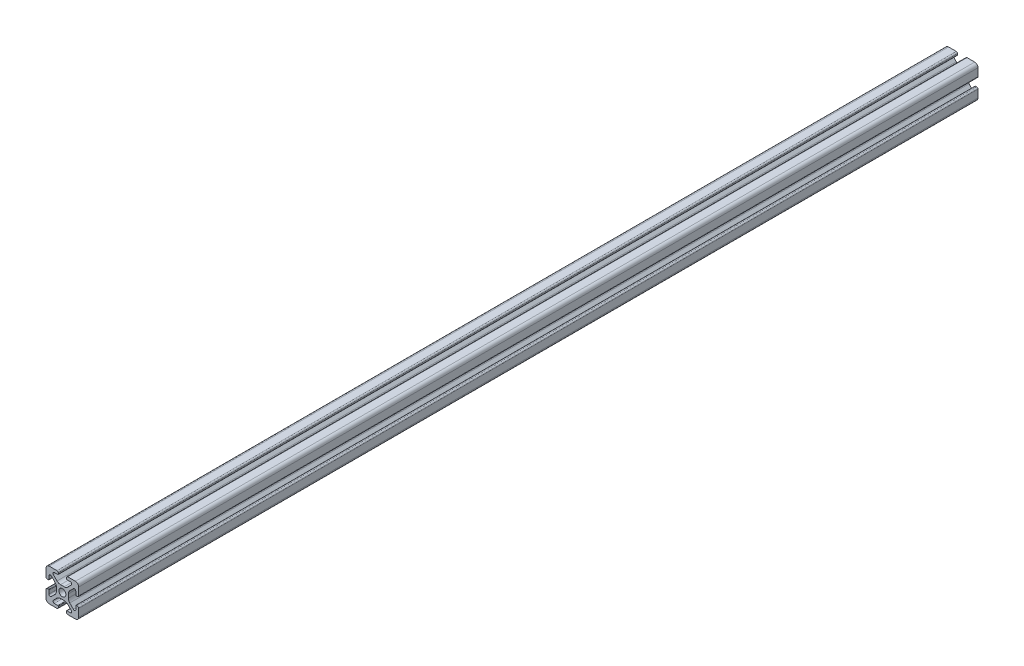
SolidWorks part; units mm, degrees
material "Alliage 1060"
ref_plane "Plan de face" through (0, 0, 0) normal (0, 0, 1) x (1, 0, 0)
ref_plane "Plan de dessus" through (0, 0, 0) normal (0, 1, 0) x (1, 0, 0)
ref_plane "Plan de droite" through (0, 0, 0) normal (1, 0, 0) x (0, 0, -1)
sketch "Esquisse1" plane through (0, 0, 0) normal (0, 0, 1) x (1, 0, 0)
  line L108 (-3.2559, 4.5287) -> (-5.5062, 6.779)
  line L109 (-4.9176, 8.2) -> (-2.8, 8.2)
  line L110 (-2.5, 8.5) -> (-2.5, 9.2)
  line L111 (-3.3, 10) -> (-8, 10)
  line L112 (-10, 8) -> (-10, 3.3)
  line L113 (-9.2, 2.5) -> (-8.5, 2.5)
  line L114 (-8.2, 2.8) -> (-8.2, 4.9176)
  line L115 (-6.779, 5.5062) -> (-4.5287, 3.2559)
  line L116 (-3.65, 1.1346) -> (-3.65, -1.1346)
  line L117 (-4.5287, -3.2559) -> (-6.779, -5.5062)
  line L118 (-8.2, -4.9176) -> (-8.2, -2.8)
  line L119 (-8.5, -2.5) -> (-9.2, -2.5)
  line L120 (-10, -3.3) -> (-10, -8)
  line L121 (-8, -10) -> (-3.3, -10)
  line L122 (-2.5, -9.2) -> (-2.5, -8.5)
  line L123 (-2.8, -8.2) -> (-4.9176, -8.2)
  line L124 (-5.5062, -6.779) -> (-3.2559, -4.5287)
  line L125 (-1.1346, -3.65) -> (1.1346, -3.65)
  line L126 (3.2559, -4.5287) -> (5.5062, -6.779)
  line L127 (4.9176, -8.2) -> (2.8, -8.2)
  line L128 (2.5, -8.5) -> (2.5, -9.2)
  line L129 (3.3, -10) -> (8, -10)
  line L130 (10, -8) -> (10, -3.3)
  line L131 (9.2, -2.5) -> (8.5, -2.5)
  line L132 (8.2, -2.8) -> (8.2, -4.9176)
  line L133 (6.779, -5.5062) -> (4.5287, -3.2559)
  line L134 (3.65, -1.1346) -> (3.65, 1.1346)
  line L135 (4.5287, 3.2559) -> (6.779, 5.5062)
  line L136 (8.2, 4.9176) -> (8.2, 2.8)
  line L137 (8.5, 2.5) -> (9.2, 2.5)
  line L138 (10, 3.3) -> (10, 8)
  line L139 (8, 10) -> (3.3, 10)
  line L140 (2.5, 9.2) -> (2.5, 8.5)
  line L141 (2.8, 8.2) -> (4.9176, 8.2)
  line L142 (5.5062, 6.779) -> (3.2559, 4.5287)
  line L143 (1.1346, 3.65) -> (-1.1346, 3.65)
  arc A42 (-2.15, 0) -> (2.15, 0) centre (0, 0) ccw
  arc A43 (2.15, 0) -> (-2.15, 0) centre (0, 0) ccw
  arc A108 (-4.9176, 8.2) -> (-5.5062, 6.779) centre (-4.9176, 7.3676) ccw
  arc A109 (-2.8, 8.2) -> (-2.5, 8.5) centre (-2.8, 8.5) ccw
  arc A110 (-2.5, 9.2) -> (-3.3, 10) centre (-3.3, 9.2) ccw
  arc A111 (-8, 10) -> (-10, 8) centre (-8, 8) ccw
  arc A112 (-10, 3.3) -> (-9.2, 2.5) centre (-9.2, 3.3) ccw
  arc A113 (-8.5, 2.5) -> (-8.2, 2.8) centre (-8.5, 2.8) ccw
  arc A114 (-6.779, 5.5062) -> (-8.2, 4.9176) centre (-7.3676, 4.9176) ccw
  arc A115 (-3.65, 1.1346) -> (-4.5287, 3.2559) centre (-6.65, 1.1346) ccw
  arc A116 (-4.5287, -3.2559) -> (-3.65, -1.1346) centre (-6.65, -1.1346) ccw
  arc A117 (-8.2, -4.9176) -> (-6.779, -5.5062) centre (-7.3676, -4.9176) ccw
  arc A118 (-8.2, -2.8) -> (-8.5, -2.5) centre (-8.5, -2.8) ccw
  arc A119 (-9.2, -2.5) -> (-10, -3.3) centre (-9.2, -3.3) ccw
  arc A120 (-10, -8) -> (-8, -10) centre (-8, -8) ccw
  arc A121 (-3.3, -10) -> (-2.5, -9.2) centre (-3.3, -9.2) ccw
  arc A122 (-2.5, -8.5) -> (-2.8, -8.2) centre (-2.8, -8.5) ccw
  arc A123 (-5.5062, -6.779) -> (-4.9176, -8.2) centre (-4.9176, -7.3676) ccw
  arc A124 (-1.1346, -3.65) -> (-3.2559, -4.5287) centre (-1.1346, -6.65) ccw
  arc A125 (3.2559, -4.5287) -> (1.1346, -3.65) centre (1.1346, -6.65) ccw
  arc A126 (4.9176, -8.2) -> (5.5062, -6.779) centre (4.9176, -7.3676) ccw
  arc A127 (2.8, -8.2) -> (2.5, -8.5) centre (2.8, -8.5) ccw
  arc A128 (2.5, -9.2) -> (3.3, -10) centre (3.3, -9.2) ccw
  arc A129 (8, -10) -> (10, -8) centre (8, -8) ccw
  arc A130 (10, -3.3) -> (9.2, -2.5) centre (9.2, -3.3) ccw
  arc A131 (8.5, -2.5) -> (8.2, -2.8) centre (8.5, -2.8) ccw
  arc A132 (6.779, -5.5062) -> (8.2, -4.9176) centre (7.3676, -4.9176) ccw
  arc A133 (3.65, -1.1346) -> (4.5287, -3.2559) centre (6.65, -1.1346) ccw
  arc A134 (4.5287, 3.2559) -> (3.65, 1.1346) centre (6.65, 1.1346) ccw
  arc A135 (8.2, 4.9176) -> (6.779, 5.5062) centre (7.3676, 4.9176) ccw
  arc A136 (8.2, 2.8) -> (8.5, 2.5) centre (8.5, 2.8) ccw
  arc A137 (9.2, 2.5) -> (10, 3.3) centre (9.2, 3.3) ccw
  arc A138 (10, 8) -> (8, 10) centre (8, 8) ccw
  arc A139 (3.3, 10) -> (2.5, 9.2) centre (3.3, 9.2) ccw
  arc A140 (2.5, 8.5) -> (2.8, 8.2) centre (2.8, 8.5) ccw
  arc A141 (5.5062, 6.779) -> (4.9176, 8.2) centre (4.9176, 7.3676) ccw
  arc A142 (1.1346, 3.65) -> (3.2559, 4.5287) centre (1.1346, 6.65) ccw
  arc A143 (-3.2559, 4.5287) -> (-1.1346, 3.65) centre (-1.1346, 6.65) ccw
extrude "Boss.-Extru.1" add sketch "Esquisse1" along normal blind 550
